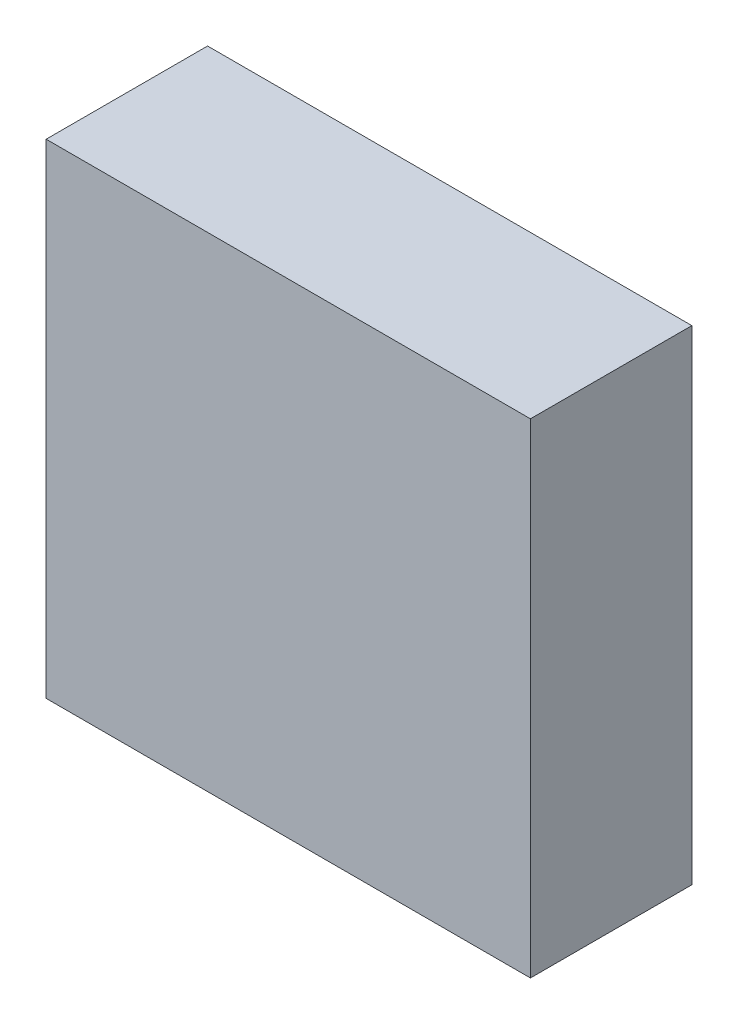
SolidWorks part; units mm, degrees
material "N38SH Neodymium Magnet"
ref_plane "Front Plane" through (0, 0, 0) normal (0, 0, 1) x (1, 0, 0)
ref_plane "Top Plane" through (0, 0, 0) normal (0, 1, 0) x (1, 0, 0)
ref_plane "Right Plane" through (0, 0, 0) normal (1, 0, 0) x (0, 0, -1)
sketch "Sketch1" plane through (0, 0, 0) normal (0, 0, 1) x (1, 0, 0)
  line L1 (-4.7625, -4.7625) -> (4.7625, -4.7625)
  line L2 (-4.7625, -4.7625) -> (-4.7625, 4.7625)
  line L3 (-4.7625, 4.7625) -> (4.7625, 4.7625)
  line L4 (4.7625, -4.7625) -> (4.7625, 4.7625)
  line L5 (-4.7625, -4.7625) -> (4.7625, 4.7625) construction
  line L6 (-4.7625, 4.7625) -> (4.7625, -4.7625) construction
  point P0 (0, 0)
  dimension "D1" = 9.525
extrude "Boss-Extrude1" add sketch "Sketch1" along normal mid plane 3.175
sketch "Sketch2" plane through (0, 0, 1.5875) normal (0, 0, 1) x (1, 0, 0)
  text T0 "4 lb"
